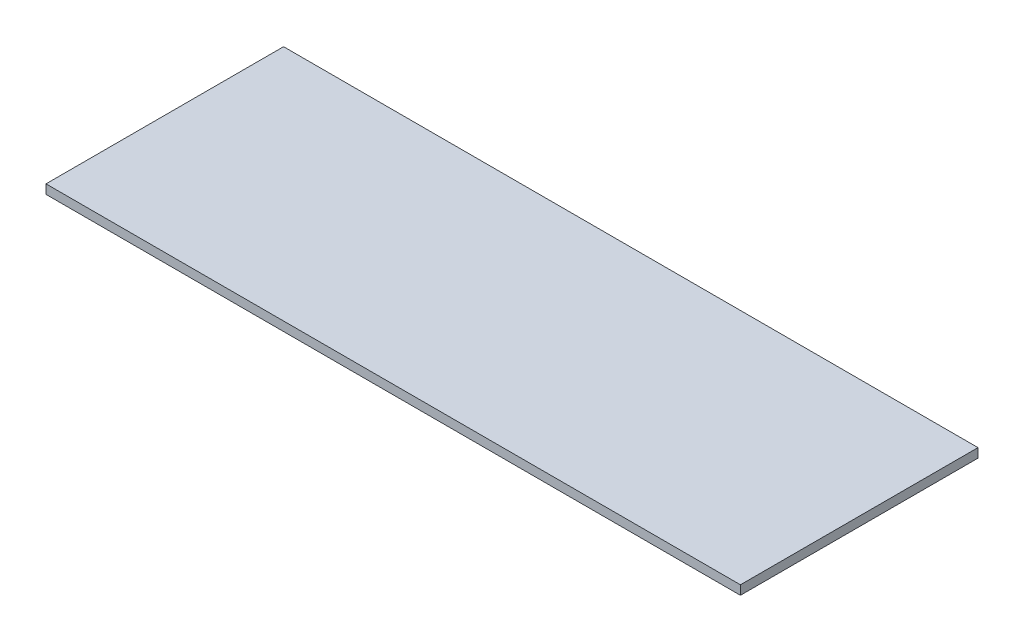
SolidWorks part; units mm, degrees
ref_plane "Front Plane" through (0, 0, 0) normal (0, 0, 1) x (1, 0, 0)
ref_plane "Top Plane" through (0, 0, 0) normal (0, 1, 0) x (1, 0, 0)
ref_plane "Right Plane" through (0, 0, 0) normal (1, 0, 0) x (0, 0, -1)
sketch "Sketch1" plane through (0, 0, 0) normal (0, 1, 0) x (1, 0, 0)
  line L1 (-39.1198, 16.3497) -> (36.8802, 16.3497)
  line L2 (-39.1198, 16.3497) -> (-39.1198, -9.6503)
  line L3 (-39.1198, -9.6503) -> (36.8802, -9.6503)
  line L4 (36.8802, 16.3497) -> (36.8802, -9.6503)
  dimension "D1" = 76
  dimension "D2" = 26
extrude "Boss-Extrude1" add sketch "Sketch1" along normal blind 1
